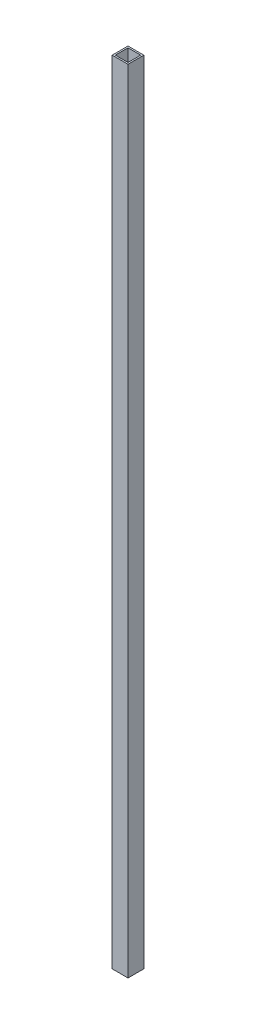
SolidWorks part; units mm, degrees
material "Thornel VCB-20 Carbon Cloth"
ref_plane "Płaszczyzna przednia" through (0, 0, 0) normal (0, 0, 1) x (1, 0, 0)
ref_plane "Płaszczyzna górna" through (0, 0, 0) normal (0, 1, 0) x (1, 0, 0)
ref_plane "Płaszczyzna prawa" through (0, 0, 0) normal (1, 0, 0) x (0, 0, -1)
sketch "Sketch1" plane through (0, 0, 0) normal (0, 1, 0) x (1, 0, 0)
  line L0 (2, 2) -> (2, 18)
  line L1 (0, 0) -> (20, 0)
  line L2 (0, 0) -> (0, 20)
  line L3 (0, 20) -> (20, 20)
  line L4 (20, 0) -> (20, 20)
  line L5 (2, 18) -> (18, 18)
  line L6 (18, 2) -> (18, 18)
  line L7 (2, 2) -> (18, 2)
  dimension "D1" = 20
  dimension "D2" = 20
  dimension "D3" = 2
extrude "Boss-Extrude1" add sketch "Sketch1" along normal blind 1000
